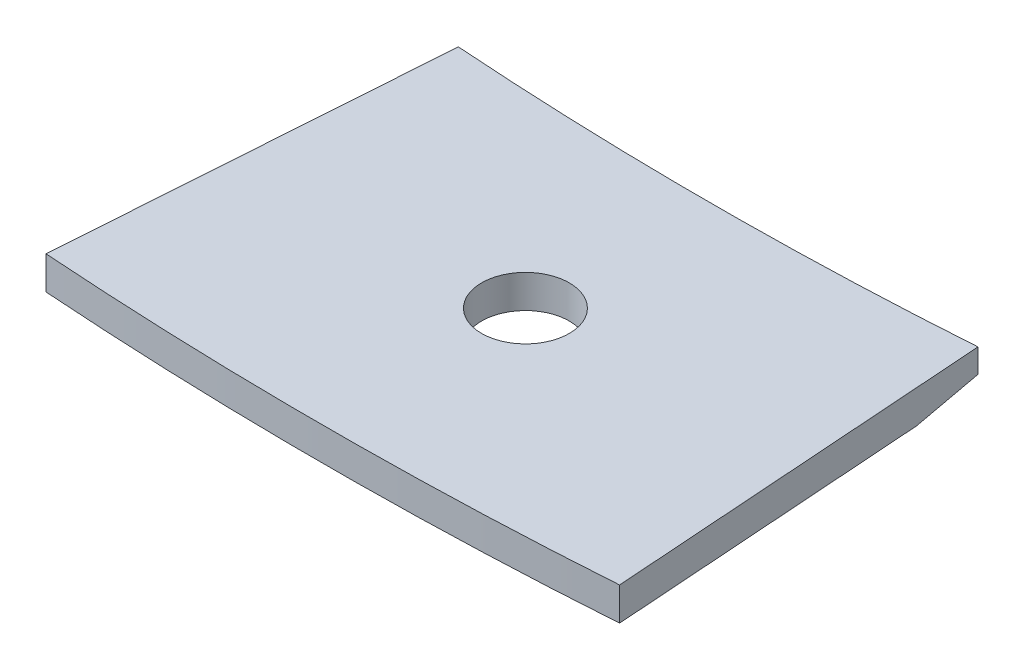
SolidWorks part; units mm, degrees
ref_plane "Front Plane" through (0, 0, 0) normal (0, 0, 1) x (1, 0, 0)
ref_plane "Top Plane" through (0, 0, 0) normal (0, 1, 0) x (1, 0, 0)
ref_plane "Right Plane" through (0, 0, 0) normal (1, 0, 0) x (0, 0, -1)
sketch "BASE" plane through (0, 0, 0) normal (0, 1, 0) x (1, 0, 0)
  line L0 (0, 0) -> (0, -243.5) construction
  line L1 (15.9742, -228.4422) -> (16.9857, -242.9068)
  line L2 (-15.9742, -228.4422) -> (-16.9857, -242.9068)
  line L3 (0, 0) -> (15.9742, -228.4422) construction
  line L4 (0, 0) -> (-15.9742, -228.4422) construction
  line L5 (0, -229) -> (0, -243.5) construction
  line L7 (-10, -226.25) -> (10, -226.25) construction
  line L8 (-10, -226.25) -> (-10, -246.25) construction
  line L9 (-10, -246.25) -> (10, -246.25) construction
  line L10 (10, -226.25) -> (10, -246.25) construction
  line L11 (-10, -226.25) -> (10, -246.25) construction
  line L12 (-10, -246.25) -> (10, -226.25) construction
  arc A0 (-16.9857, -242.9068) -> (16.9857, -242.9068) centre (0, 0) ccw
  arc A1 (-15.9742, -228.4422) -> (15.9742, -228.4422) centre (0, 0) ccw
  circle A2 centre (0, -236.25) radius 2.65
  dimension "D1" = 487
  dimension "D2" = 14.5
  dimension "D6" = 5.3
  dimension "D3" = 4
  dimension "D4" = 4
  dimension "D5" = 20
sketch "Sketch2" plane through (0, 0, 0) normal (0, 1, 0) x (1, 0, 0)
  line L1 (-15.9742, -228.4422) -> (-16.9857, -242.9068) construction
  line L3 (15.9742, -228.4422) -> (16.9857, -242.9068) construction
  line L4 (0, 0) -> (-17.3345, -247.8947) construction
  line L5 (0, 0) -> (17.3345, -247.8947) construction
  line L6 (-15.9847, -228.5918) -> (-17.3345, -247.8947)
  line L7 (15.9847, -228.5918) -> (17.3345, -247.8947)
  arc A0 (15.9847, -228.5918) -> (-15.9847, -228.5918) centre (0, 0) cw
  arc A1 (-15.9742, -228.4422) -> (15.9742, -228.4422) centre (0, 0) ccw construction
  arc A2 (17.3345, -247.8947) -> (-17.3345, -247.8947) centre (0, 0) cw
  arc A3 (-16.9857, -242.9068) -> (16.9857, -242.9068) centre (0, 0) ccw construction
  circle A4 centre (0, -236.25) radius 2.65
  dimension "D1" = 0.15
  dimension "D2" = 5
  dimension "D3" = 5.3
extrude "Boss-Extrude1" add sketch "Sketch2" along normal blind 2
sketch "Sketch3" plane through (0, 0, 0) normal (0, 1, 0) x (1, 0, 0)
  line L0 (0, 0) -> (15.9742, -228.4422) construction
  line L1 (0, 0) -> (-15.9742, -228.4422) construction
  line L2 (-15.7057, -224.6015) -> (-15.9847, -228.5918)
  line L3 (15.7057, -224.6015) -> (15.9847, -228.5918)
  arc A0 (15.9847, -228.5918) -> (-15.9847, -228.5918) centre (0, 0) cw
  arc A1 (15.7057, -224.6015) -> (-15.7057, -224.6015) centre (0, 0) cw
  dimension "D1" = 4
extrude "Boss-Extrude2" add sketch "Sketch3" against normal blind 2 from surface at 2 starting at face at (0, 2, 238.5341)
chamfer "Chamfer1" distance 4 angle 8 1 edges at (0, 0, 225.15)
